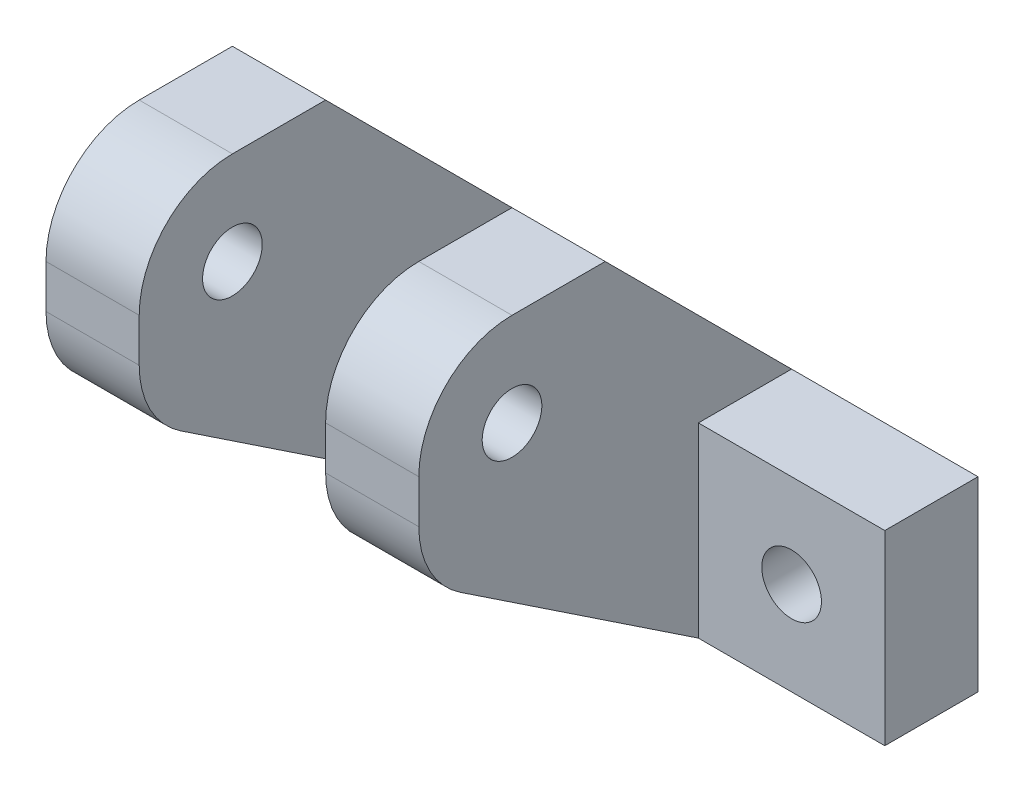
SolidWorks part; units mm, degrees
ref_plane "正面" through (0, 0, 0) normal (0, 0, 1) x (1, 0, 0)
ref_plane "平面" through (0, 0, 0) normal (0, 1, 0) x (1, 0, 0)
ref_plane "右側面" through (0, 0, 0) normal (1, 0, 0) x (0, 0, -1)
sketch "Sketch1" plane through (0, 0, 0) normal (0, 0, 1) x (1, 0, 0)
  line L1 (-20, 5) -> (20, 5)
  line L2 (-20, 5) -> (-20, -5)
  line L3 (-20, -5) -> (20, -5)
  line L4 (20, 5) -> (20, -5)
  line L5 (-20, 5) -> (20, -5) construction
  line L6 (-20, -5) -> (20, 5) construction
  point P0 (0, 0)
  dimension "D1" = 40
  dimension "D2" = 10
extrude "Boss-Extrude1" add sketch "Sketch1" along normal blind 5
sketch "Sketch2" plane through (0, 0, 5) normal (0, 0, 1) x (1, 0, 0)
  line L0 (0, 5) -> (0, -5) construction
  line L1 (20, 5) -> (-20, 5) construction
  line L2 (-20, -5) -> (20, -5) construction
  line L3 (-5, -5) -> (-10, -5)
  line L4 (5, 5) -> (10, 5)
  line L5 (5, 5) -> (5, -5)
  line L6 (5, -5) -> (10, -5)
  line L7 (10, 5) -> (10, -5)
  line L8 (-10, 5) -> (-10, -5)
  line L9 (-5, 5) -> (-10, 5)
  line L10 (-5, 5) -> (-5, -5)
  dimension "D1" = 5
  dimension "D2" = 5
extrude "Boss-Extrude2" add sketch "Sketch2" along normal blind 15
sketch "Sketch4" plane through (0, 0, 0) normal (0, 0, -1) x (-1, 0, 0)
  line L0 (-20, 0) -> (20, 0) construction
  line L1 (-20, -5) -> (-20, 5) construction
  line L2 (20, 5) -> (20, -5) construction
  line L3 (0, 5) -> (0, -5) construction
  line L4 (-20, 5) -> (20, 5) construction
  line L5 (20, -5) -> (-20, -5) construction
  circle A0 centre (-15, 0) radius 1.6
  circle A1 centre (15, 0) radius 1.6
  dimension "D1" = 3.2
  dimension "D2" = 5
extrude "Cut-Extrude2" cut sketch "Sketch4" against normal blind 15
sketch "Sketch5" plane through (0, 5, 0) normal (0, 1, 0) x (1, 0, 0)
  line L0 (20, 0) -> (-20, 0) construction
  line L1 (-10, -20) -> (-5, -20)
  line L2 (-10, -20) -> (-10, 0)
  line L3 (-10, 0) -> (-5, 0)
  line L4 (-5, -20) -> (-5, 0)
  line L6 (5, -20) -> (10, -20)
  line L7 (5, -20) -> (5, 0)
  line L8 (5, 0) -> (10, 0)
  line L9 (10, -20) -> (10, 0)
  dimension "D1" = 5
  dimension "D2" = 5
extrude "Boss-Extrude3" add sketch "Sketch5" along normal blind 10
sketch "Sketch6" plane through (-10, 0, 0) normal (-1, 0, 0) x (0, 0, 1)
  line L0 (0, 10) -> (20, 10) construction
  line L1 (0, 15) -> (0, 5) construction
  line L2 (20, 15) -> (20, -5) construction
  line L3 (0, 15) -> (20, 15) construction
  circle A0 centre (15, 10) radius 1.6
  dimension "D3" = 3.2
  dimension "D1" = 5
  dimension "D2" = 5
extrude "Cut-Extrude3" cut sketch "Sketch6" against normal up to surface (20 mm away) up to face at (10, 5, 8.3333)
sketch "Sketch7" plane through (-10, 0, 0) normal (-1, 0, 0) x (0, 0, 1)
  line L0 (20, 5) -> (5, -5)
  line L1 (20, 15) -> (20, -5) construction
  line L2 (5, -5) -> (20, -5)
  line L3 (20, -5) -> (20, 5)
extrude "Cut-Extrude4" cut sketch "Sketch7" against normal up to surface (20 mm away) up to face at (10, 10, 16.6)
fillet "Fillet2" radius 5 4 edges at (7.5, 5, 20) (-7.5, 5, 20) (7.5, 15, 20) (-7.5, 15, 20)
sketch "Sketch8" plane through (-10, 0, 0) normal (-1, 0, 0) x (0, 0, 1)
  line L0 (0, 5) -> (10, 15)
  line L1 (0, 15) -> (15, 15) construction
  line L2 (10, 15) -> (0, 15)
  line L3 (0, 15) -> (0, 5)
  dimension "D1" = 10
extrude "Cut-Extrude5" cut sketch "Sketch8" against normal up to surface (20 mm away) up to face at (10, 10, 16.6)
